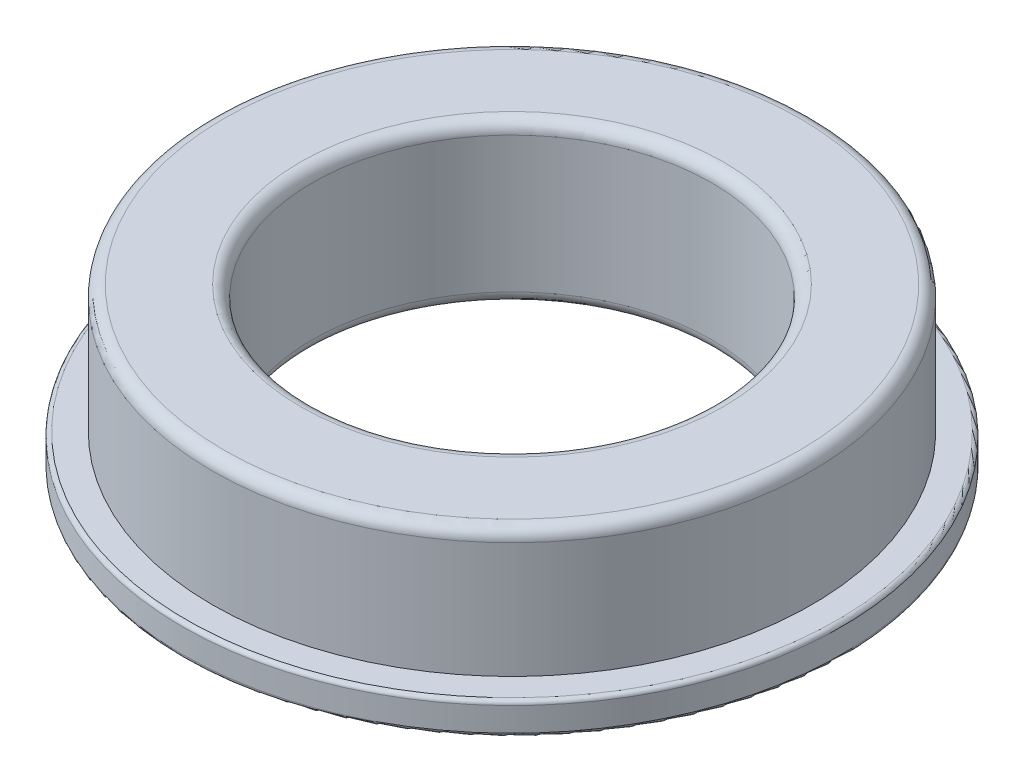
SolidWorks part; units mm, degrees
ref_plane "Front Plane" through (0, 0, 0) normal (0, 0, 1) x (1, 0, 0)
ref_plane "Top Plane" through (0, 0, 0) normal (0, 1, 0) x (1, 0, 0)
ref_plane "Right Plane" through (0, 0, 0) normal (1, 0, 0) x (0, 0, -1)
sketch "Sketch1" plane through (0, 0, 0) normal (0, 1, 0) x (1, 0, 0)
  circle A0 centre (0, 0) radius 7.5
  circle A1 centre (0, 0) radius 5
  point P5 (-0.2294, 0)
  dimension "D1" = 10
  dimension "D2" = 15
extrude "Boss-Extrude1" add sketch "Sketch1" along normal blind 4
sketch "Sketch2" plane through (0, 0, 0) normal (0, -1, 0) x (1, 0, 0)
  circle A0 centre (0, 0) radius 8.25
  circle A1 centre (0, 0) radius 5
  circle A2 centre (0, 0) radius 5 construction
  dimension "D1" = 16.5
extrude "Boss-Extrude2" add sketch "Sketch2" against normal blind 0.8
fillet "Fillet1" radius 0.3 3 edges at (0, 4, 5) (0, 0, 5) (0, 4, 7.5)
fillet "Fillet2" radius 0.1 2 edges at (0, 0.8, -8.25) (0, 0, -8.25)
